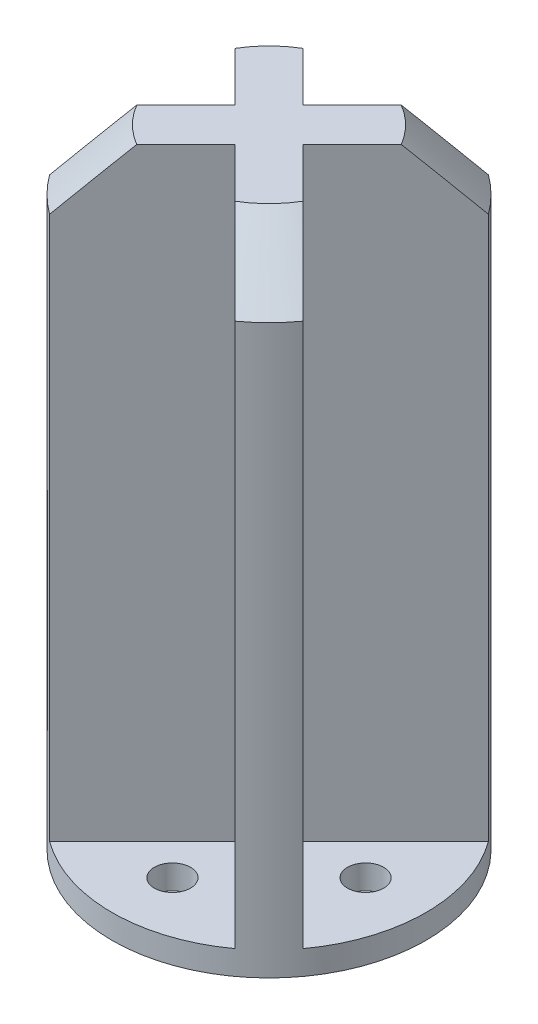
SolidWorks part; units mm, degrees
ref_plane "Front Plane" through (0, 0, 0) normal (0, 0, 1) x (1, 0, 0)
ref_plane "Top Plane" through (0, 0, 0) normal (0, 1, 0) x (1, 0, 0)
ref_plane "Right Plane" through (0, 0, 0) normal (1, 0, 0) x (0, 0, -1)
sketch "Sketch1" plane through (0, 0, 0) normal (0, 1, 0) x (1, 0, 0)
  circle A0 centre (0, 0) radius 13
  dimension "D1" = 26
extrude "Boss-Extrude1" add sketch "Sketch1" along normal blind 2
sketch "Sketch2" plane through (0, 2, 0) normal (0, 1, 0) x (1, 0, 0)
  line L0 (-13, 0) -> (13, 0) construction
  circle A0 centre (0, 0) radius 13 construction
  circle A1 centre (-8, 0) radius 1.5
  circle A2 centre (0, 8) radius 1.5
  circle A3 centre (8, 0) radius 1.5
  circle A4 centre (0, -8) radius 1.5
  point P7 (0, 0)
  point P10 (0.0264, 1.057)
  point P17 (0, 0)
  dimension "D1" = 3
  dimension "D2" = 8
  dimension "D3" = 4
extrude "Cut-Extrude1" cut sketch "Sketch2" against normal through all
sketch "Sketch3" plane through (0, 2, 0) normal (0, 1, 0) x (1, 0, 0)
  line L0 (-9.1924, 9.1924) -> (9.1924, -9.1924) construction
  line L1 (-9.1924, -9.1924) -> (9.1924, 9.1924) construction
  line L2 (-9.1924, 9.1924) -> (-9.1924, -9.1924) construction
  line L3 (-9.1924, -9.1924) -> (9.1924, -9.1924) construction
  line L4 (-10.4972, 7.6687) -> (-2.8284, 0)
  line L5 (-7.6687, 10.4972) -> (0, 2.8284)
  line L6 (7.6687, 10.4972) -> (0, 2.8284)
  line L7 (10.4972, 7.6687) -> (2.8284, 0)
  line L8 (10.4972, -7.6687) -> (2.8284, 0)
  line L9 (7.6687, -10.4972) -> (0, -2.8284)
  line L10 (-7.6687, -10.4972) -> (0, -2.8284)
  line L11 (-10.4972, -7.6687) -> (-2.8284, 0)
  line L12 (-2.8284, 0) -> (-10.4972, -7.6687)
  line L13 (0, 2.8284) -> (7.6904, 10.5188)
  line L14 (2.8284, 0) -> (10.4972, -7.6687)
  line L15 (0, 2.8284) -> (-7.6687, 10.4972)
  line L16 (0, -2.8284) -> (-7.6687, -10.4972)
  line L17 (2.8284, 0) -> (10.5188, 7.6904)
  line L18 (-2.8284, 0) -> (-10.4972, 7.6687)
  line L19 (0, -2.8284) -> (7.6687, -10.4972)
  circle A0 centre (0, 0) radius 13 construction
  arc A2 (-7.6687, 10.4972) -> (-10.4972, 7.6687) centre (0, 0) ccw
  arc A3 (10.4972, 7.6687) -> (7.6687, 10.4972) centre (0, 0) ccw
  arc A5 (7.6687, -10.4972) -> (10.4972, -7.6687) centre (0, 0) ccw
  arc A6 (-7.6687, 10.4972) -> (-10.4972, 7.6687) centre (0, 0) ccw
  arc A7 (-10.4972, -7.6687) -> (-7.6687, -10.4972) centre (0, 0) ccw
  arc A8 (10.5188, 7.6904) -> (7.6904, 10.5188) centre (0, 0) ccw
  point P12 (-3.2683, 0.4398)
  point P15 (0, 0)
  point P17 (-10.4972, -7.6687)
  point P26 (0, 0)
  point P29 (0, 0)
  point P30 (-2.8284, 0)
  point P31 (0.401, -3.2294)
  point P32 (0, 0)
  circle M14 centre (0, 0) radius 13
  dimension "D1" = 4
extrude "Boss-Extrude2" add sketch "Sketch3" along normal blind 50 contours L11 L10 L9 L8 L7 L6 L5 L4 M14
chamfer "Chamfer1" distance 5 angle 45 4 edges at (-9.1924, 52, 9.1924) (9.1924, 52, -9.1924) (9.1924, 52, 9.1924) (-9.1924, 52, -9.1924)
